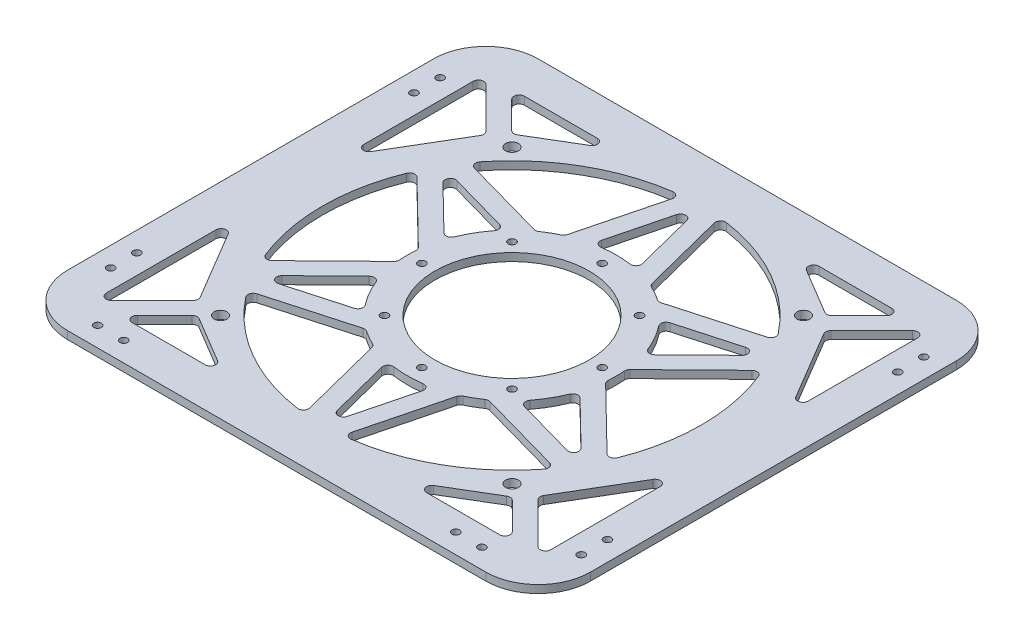
SolidWorks part; units mm, degrees
material "Thornel Mat VMA"
ref_plane "前视基准面" through (0, 0, 0) normal (0, 0, 1) x (1, 0, 0)
ref_plane "上视基准面" through (0, 0, 0) normal (0, 1, 0) x (1, 0, 0)
ref_plane "右视基准面" through (0, 0, 0) normal (1, 0, 0) x (0, 0, -1)
other "Configuration Table"
sketch "草图1" plane through (0, 0, 0) normal (0, 1, 0) x (1, 0, 0)
  line L0 (55.7412, 55.7412) -> (0, 0) construction
  line L1 (0, 0) -> (78.83, 0) construction
  line L2 (-117.6267, -82.5) -> (139.5977, -82.5) construction
  line L3 (-100, -90) -> (100, -90)
  line L4 (-100, -90) -> (-100, 90)
  line L5 (-100, 90) -> (100, 90)
  line L6 (100, -90) -> (100, 90)
  line L7 (-100, -90) -> (100, 90) construction
  line L8 (-100, 90) -> (100, -90) construction
  circle A0 centre (0, 0) radius 78.83 construction
  circle A1 centre (55.7412, 55.7412) radius 2.45
  circle A5 centre (55.7412, -55.7412) radius 2.45
  circle A6 centre (-55.7412, -55.7412) radius 2.45
  circle A7 centre (-55.7412, 55.7412) radius 2.45
  circle A8 centre (0, 0) radius 105 construction
  dimension "D1" = 157.66
  dimension "D2" = 4.9
  dimension "D6" = 210
  dimension "D8" = 180
  dimension "D3" = 45
  dimension "D5" = 200
  dimension "D7" = 7.5
  dimension "D4" = 4
extrude "凸台-拉伸1" add sketch "草图1" along normal blind 3
sketch "草图2" plane through (0, 3, 0) normal (0, 1, 0) x (1, 0, 0)
  circle A0 centre (0, 0) radius 34.5 construction
  circle A1 centre (0, 34.5) radius 1.45
  circle A2 centre (24.3952, 24.3952) radius 1.45
  circle A3 centre (34.5, 0) radius 1.45
  circle A4 centre (24.3952, -24.3952) radius 1.45
  circle A5 centre (0, -34.5) radius 1.45
  circle A6 centre (-24.3952, -24.3952) radius 1.45
  circle A7 centre (-34.5, 0) radius 1.45
  circle A8 centre (-24.3952, 24.3952) radius 1.45
  circle A9 centre (0, 0) radius 29.5
  point P22 (0, 0)
  dimension "D1" = 2.9
  dimension "D2" = 69
  dimension "D4" = 5
  dimension "D3" = 8
extrude "切除-拉伸1" cut sketch "草图2" against normal through all
sketch "草图3" plane through (0, 3, 0) normal (0, 1, 0) x (1, 0, 0)
  line L0 (-32.7307, 64.6912) -> (-16.4356, 36.4674)
  line L5 (-16.4356, 36.4674) -> (-7.3198, 72.1295)
  line L11 (0, 72.5) -> (8.5435, 39.077)
  line L40 (0, 72.5) -> (-8.5435, 39.077)
  line L48 (16.4356, 36.4674) -> (7.3198, 72.1295)
  line L49 (32.7307, 64.6912) -> (16.4356, 36.4674)
  line L58 (-1000, 0) -> (49000, 0) construction
  line L59 (0, -1000) -> (0, 49000) construction
  line L62 (85, -75) -> (85, 75)
  line L63 (85, 75) -> (-85, 75)
  line L64 (-85, 75) -> (-85, -75)
  line L65 (-85, -75) -> (85, -75)
  line L66 (85, -75) -> (85, 75) construction
  line L71 (85, 75) -> (-85, 75) construction
  line L72 (-85, 75) -> (-85, -75) construction
  line L73 (-85, -75) -> (85, -75) construction
  line L80 (-85, 75) -> (-64.8957, 54.8957)
  line L81 (-36.25, 62.7868) -> (-20, 34.641) construction
  line L82 (-39.6589, 60.6912) -> (-23.3639, 32.4674)
  line L83 (-72.3896, 4) -> (-39.7995, 4)
  line L84 (-23.3639, 32.4674) -> (-58.8061, 42.4039)
  line L85 (-39.7995, 4) -> (-66.1259, 29.7257)
  line L86 (-62.7868, 36.25) -> (-38.1134, 12.1396)
  line L87 (-62.7868, 36.25) -> (-29.5699, 26.9374)
  line L88 (39.6589, 60.6912) -> (23.3639, 32.4674)
  line L89 (23.3639, 32.4674) -> (58.8061, 42.4039)
  line L90 (62.7868, 36.25) -> (38.1134, 12.1396)
  line L91 (62.7868, 36.25) -> (29.5699, 26.9374)
  line L92 (39.7995, 4) -> (66.1259, 29.7257)
  line L93 (72.3896, 4) -> (39.7995, 4)
  line L94 (72.3896, -4) -> (39.7995, -4)
  line L95 (39.7995, -4) -> (66.1259, -29.7257)
  line L96 (62.7868, -36.25) -> (29.5699, -26.9374)
  line L97 (62.7868, -36.25) -> (38.1134, -12.1396)
  line L98 (23.3639, -32.4674) -> (58.8061, -42.4039)
  line L99 (39.6589, -60.6912) -> (23.3639, -32.4674)
  line L100 (32.7307, -64.6912) -> (16.4356, -36.4674)
  line L101 (16.4356, -36.4674) -> (7.3198, -72.1295)
  line L102 (0, -72.5) -> (-8.5435, -39.077)
  line L103 (0, -72.5) -> (8.5435, -39.077)
  line L104 (-16.4356, -36.4674) -> (-7.3198, -72.1295)
  line L105 (-32.7307, -64.6912) -> (-16.4356, -36.4674)
  line L106 (-39.6589, -60.6912) -> (-23.3639, -32.4674)
  line L107 (-23.3639, -32.4674) -> (-58.8061, -42.4039)
  line L108 (-62.7868, -36.25) -> (-38.1134, -12.1396)
  line L109 (-62.7868, -36.25) -> (-29.5699, -26.9374)
  line L110 (-39.7995, -4) -> (-66.1259, -29.7257)
  line L111 (-72.3896, -4) -> (-39.7995, -4)
  line L114 (0, 0) -> (-82.2862, 82.2862) construction
  line L115 (-64.8957, 54.8957) -> (-85, 21)
  line L116 (-85, 21) -> (-85, 75)
  line L138 (-75.1005, 75) -> (-60.1543, 60.0538)
  line L139 (-60.1543, 60.0538) -> (-35.1005, 75)
  line L140 (-35.1005, 75) -> (-75.1005, 75)
  line L141 (64.8957, 54.8957) -> (85, 21)
  line L142 (85, 75) -> (64.8957, 54.8957)
  line L143 (85, 21) -> (85, 75)
  line L144 (60.1543, 60.0538) -> (35.1005, 75)
  line L145 (75.1005, 75) -> (60.1543, 60.0538)
  line L146 (35.1005, 75) -> (75.1005, 75)
  line L147 (85, -75) -> (64.8957, -54.8957)
  line L148 (85, -21) -> (85, -75)
  line L149 (64.8957, -54.8957) -> (85, -21)
  line L150 (75.1005, -75) -> (60.1543, -60.0538)
  line L151 (35.1005, -75) -> (75.1005, -75)
  line L152 (60.1543, -60.0538) -> (35.1005, -75)
  line L153 (-60.1543, -60.0538) -> (-35.1005, -75)
  line L154 (-75.1005, -75) -> (-60.1543, -60.0538)
  line L155 (-35.1005, -75) -> (-75.1005, -75)
  line L156 (-64.8957, -54.8957) -> (-85, -21)
  line L157 (-85, -75) -> (-64.8957, -54.8957)
  line L158 (-85, -21) -> (-85, -75)
  circle A52 centre (0, 0) radius 40 construction
  circle A53 centre (0, 0) radius 72.5 construction
  circle A54 centre (0, 0) radius 85 construction
  circle A55 centre (0, 0) radius 100 construction
  arc A65 (-39.6589, 60.6912) -> (-58.8061, 42.4039) centre (0, 0) ccw
  arc A66 (-38.1134, 12.1396) -> (-29.5699, 26.9374) centre (0, 0) cw
  arc A67 (-66.1259, 29.7257) -> (-72.3896, 4) centre (0, 0) ccw
  arc A68 (-7.3198, 72.1295) -> (-32.7307, 64.6912) centre (0, 0) ccw
  arc A69 (-8.5435, 39.077) -> (8.5435, 39.077) centre (0, 0) cw
  arc A70 (32.7307, 64.6912) -> (7.3198, 72.1295) centre (0, 0) ccw
  arc A71 (58.8061, 42.4039) -> (39.6589, 60.6912) centre (0, 0) ccw
  arc A72 (29.5699, 26.9374) -> (38.1134, 12.1396) centre (0, 0) cw
  arc A73 (72.3896, 4) -> (66.1259, 29.7257) centre (0, 0) ccw
  arc A74 (66.1259, -29.7257) -> (72.3896, -4) centre (0, 0) ccw
  arc A75 (38.1134, -12.1396) -> (29.5699, -26.9374) centre (0, 0) cw
  arc A76 (39.6589, -60.6912) -> (58.8061, -42.4039) centre (0, 0) ccw
  arc A77 (7.3198, -72.1295) -> (32.7307, -64.6912) centre (0, 0) ccw
  arc A78 (8.5435, -39.077) -> (-8.5435, -39.077) centre (0, 0) cw
  arc A79 (-32.7307, -64.6912) -> (-7.3198, -72.1295) centre (0, 0) ccw
  arc A80 (-58.8061, -42.4039) -> (-39.6589, -60.6912) centre (0, 0) ccw
  arc A81 (-29.5699, -26.9374) -> (-38.1134, -12.1396) centre (0, 0) cw
  arc A82 (-72.3896, -4) -> (-66.1259, -29.7257) centre (0, 0) ccw
  point P95 (0, 0)
  dimension "D1" = 80
  dimension "D5" = 15
  dimension "D4" = 200
  dimension "D12" = 54
  dimension "D13" = 40
  dimension "D2" = 145
  dimension "D3" = 170
  dimension "D11" = 45
  dimension "D6" = 4
  dimension "D8" = 4
  dimension "D9" = 7
  dimension "D7" = 60
  dimension "D10" = 7
extrude "切除-拉伸4" cut sketch "草图3" against normal through all
sketch "草图5" plane through (0, 3, 0) normal (0, 1, 0) x (1, 0, 0)
  line L0 (-39.7995, -4) -> (-72.3896, -4) construction
  line L1 (-72.3896, 4) -> (-39.7995, 4)
  line L2 (-72.3896, -4) -> (-39.7995, -4)
  line L3 (-39.6589, 60.6912) -> (-23.3639, 32.4674)
  line L4 (-32.7307, 64.6912) -> (-16.4356, 36.4674)
  line L5 (32.7307, 64.6912) -> (16.4356, 36.4674)
  line L6 (39.6589, 60.6912) -> (23.3639, 32.4674)
  line L7 (72.3896, 4) -> (39.7995, 4)
  line L8 (72.3896, -4) -> (39.7995, -4)
  line L9 (39.6589, -60.6912) -> (23.3639, -32.4674)
  line L10 (32.7307, -64.6912) -> (16.4356, -36.4674)
  line L11 (-32.7307, -64.6912) -> (-16.4356, -36.4674)
  line L12 (-39.6589, -60.6912) -> (-23.3639, -32.4674)
  arc A0 (-72.3896, 4) -> (-72.3896, -4) centre (0, 0) ccw
  arc A1 (-72.3896, -4) -> (-66.1259, -29.7257) centre (0, 0) ccw construction
  arc A2 (-39.7995, 4) -> (-39.7995, -4) centre (0, 0) ccw
  arc A3 (-16.4356, 36.4674) -> (-23.3639, 32.4674) centre (0, 0) ccw
  arc A4 (-32.7307, 64.6912) -> (-39.6589, 60.6912) centre (0, 0) ccw
  arc A5 (23.3639, 32.4674) -> (16.4356, 36.4674) centre (0, 0) ccw
  arc A6 (39.6589, 60.6912) -> (32.7307, 64.6912) centre (0, 0) ccw
  arc A7 (39.7995, -4) -> (39.7995, 4) centre (0, 0) ccw
  arc A8 (72.3896, -4) -> (72.3896, 4) centre (0, 0) ccw
  arc A9 (16.4356, -36.4674) -> (23.3639, -32.4674) centre (0, 0) ccw
  arc A10 (32.7307, -64.6912) -> (39.6589, -60.6912) centre (0, 0) ccw
  arc A11 (-23.3639, -32.4674) -> (-16.4356, -36.4674) centre (0, 0) ccw
  arc A12 (-39.6589, -60.6912) -> (-32.7307, -64.6912) centre (0, 0) ccw
  circle A13 centre (0, 0) radius 29.5 construction
  dimension "D1" = 6
extrude "切除-拉伸6" cut sketch "草图5" against normal through all
fillet "圆角2" radius 20 4 edges at (-100, 1.5, 90) (-100, 1.5, -90) (100, 1.5, -90) (100, 1.5, 90)
fillet "圆角3" radius 2 66 edges at (0, 1.5, 72.5) (-8.5435, 1.5, 39.077) (8.5435, 1.5, 39.077) (7.3198, 1.5, 72.1295) (-66.1259, 1.5, 29.7257) (-58.8061, 1.5, 42.4039) (-62.7868, 1.5, 36.25) (-38.1134, 1.5, 12.1396) (-29.5699, 1.5, 26.9374) (-7.3198, 1.5, -72.1295) (7.3198, 1.5, -72.1295) (-66.1259, 1.5, -29.7257) (-29.5699, 1.5, -26.9374) (-38.1134, 1.5, -12.1396) (-62.7868, 1.5, -36.25) (-58.8061, 1.5, -42.4039) (58.8061, 1.5, -42.4039) (62.7868, 1.5, -36.25) (38.1134, 1.5, -12.1396) (29.5699, 1.5, -26.9374) (66.1259, 1.5, -29.7257) (0, 1.5, -72.5) (8.5435, 1.5, -39.077) (-8.5435, 1.5, -39.077) (-7.3198, 1.5, 72.1295) (62.7868, 1.5, 36.25) (29.5699, 1.5, 26.9374) (38.1134, 1.5, 12.1396) (66.1259, 1.5, 29.7257) (58.8061, 1.5, 42.4039) (-85, 1.5, -75) (-64.8957, 1.5, -54.8957) (-85, 1.5, -21) (-60.1543, 1.5, -60.0538) (-75.1005, 1.5, -75) (-60.1543, 1.5, 60.0538) (-35.1005, 1.5, 75) (-75.1005, 1.5, 75) (35.1005, 1.5, 75) (60.1543, 1.5, 60.0538) (75.1005, 1.5, 75) (60.1543, 1.5, -60.0538) (35.1005, 1.5, -75) (75.1005, 1.5, -75) (85, 1.5, 75) (64.8957, 1.5, 54.8957) (85, 1.5, 21) (85, 1.5, -21) (64.8957, 1.5, -54.8957) (85, 1.5, -75) (-85, 1.5, 21) (-64.8957, 1.5, 54.8957) (-85, 1.5, 75) (-35.1005, 1.5, -75) (-16.4356, 1.5, -36.4674) (-23.3639, 1.5, -32.4674) (23.3639, 1.5, -32.4674) (16.4356, 1.5, -36.4674) (39.7995, 1.5, 4) (39.7995, 1.5, -4) (16.4356, 1.5, 36.4674) (23.3639, 1.5, 32.4674) (-23.3639, 1.5, 32.4674) (-16.4356, 1.5, 36.4674) (-39.7995, 1.5, 4) (-39.7995, 1.5, -4)
sketch "草图4" plane through (0, 3, 0) normal (0, 1, 0) x (1, 0, 0)
  line L0 (-100, 70) -> (-100, -70) construction
  line L1 (-100, -2.4489) -> (-85, -2.4489) construction
  line L2 (-100, -2.4489) -> (-100, -89.9767) construction
  line L3 (-100, -89.9767) -> (-85, -89.9767) construction
  line L4 (-85, -2.4489) -> (-85, -89.9767) construction
  line L5 (100, -70) -> (100, 70) construction
  line L6 (-100, -75) -> (100, -75) construction
  line L7 (-100, -75) -> (-100, -90) construction
  line L8 (-100, -90) -> (100, -90) construction
  line L9 (100, -75) -> (100, -90) construction
  line L10 (-70.2721, -75) -> (-42.3568, -75) construction
  line L11 (85, -70.1716) -> (85, -28.2925) construction
  line L12 (100, -90) -> (85, -90) construction
  line L13 (100, -90) -> (100, -32.8512) construction
  line L14 (100, -32.8512) -> (85, -32.8512) construction
  line L15 (85, -90) -> (85, -32.8512) construction
  line L16 (-92.5, -2.4489) -> (-92.5, -89.9767) construction
  line L17 (100, -82.5) -> (-100, -82.5) construction
  line L18 (92.5, -32.8512) -> (92.5, -90) construction
  line L19 (-80, 90) -> (-102.0103, 90) construction
  line L20 (-92.5, 29.7662) -> (-92.5, 90) construction
  line L21 (67.3956, 90) -> (114.2921, 90) construction
  line L22 (80, 90) -> (-80, 90) construction
  line L23 (92.5, 32.5342) -> (92.5, 90) construction
  line L24 (70.2721, 75) -> (42.3568, 75) construction
  line L25 (-42.3568, 75) -> (-70.2721, 75) construction
  circle A0 centre (-92.5, -61) radius 1.45
  circle A1 centre (-92.5, -51) radius 1.45
  circle A2 centre (-76, -82.5) radius 1.45
  circle A3 centre (-66, -82.5) radius 1.45
  circle A4 centre (61, -82.5) radius 1.45
  circle A5 centre (71, -82.5) radius 1.45
  circle A6 centre (92.5, -66) radius 1.45
  circle A7 centre (92.5, -56) radius 1.45
  circle A8 centre (-92.5, 55) radius 1.45
  circle A9 centre (-92.5, 65) radius 1.45
  circle A10 centre (92.5, 65) radius 1.45
  circle A11 centre (92.5, 55) radius 1.45
  dimension "D3" = 14
  dimension "D4" = 10
  dimension "D5" = 9
  dimension "D6" = 10
  dimension "D7" = 2.9
  dimension "D8" = 14
  dimension "D9" = 10
  dimension "D10" = 9
  dimension "D11" = 10
  dimension "D13" = 10
  dimension "D14" = 10
  dimension "D15" = 10
  dimension "D16" = 2.9
  dimension "D1" = 15
  dimension "D2" = 15
  dimension "D12" = 10
extrude "切除-拉伸5" cut sketch "草图4" against normal through all
